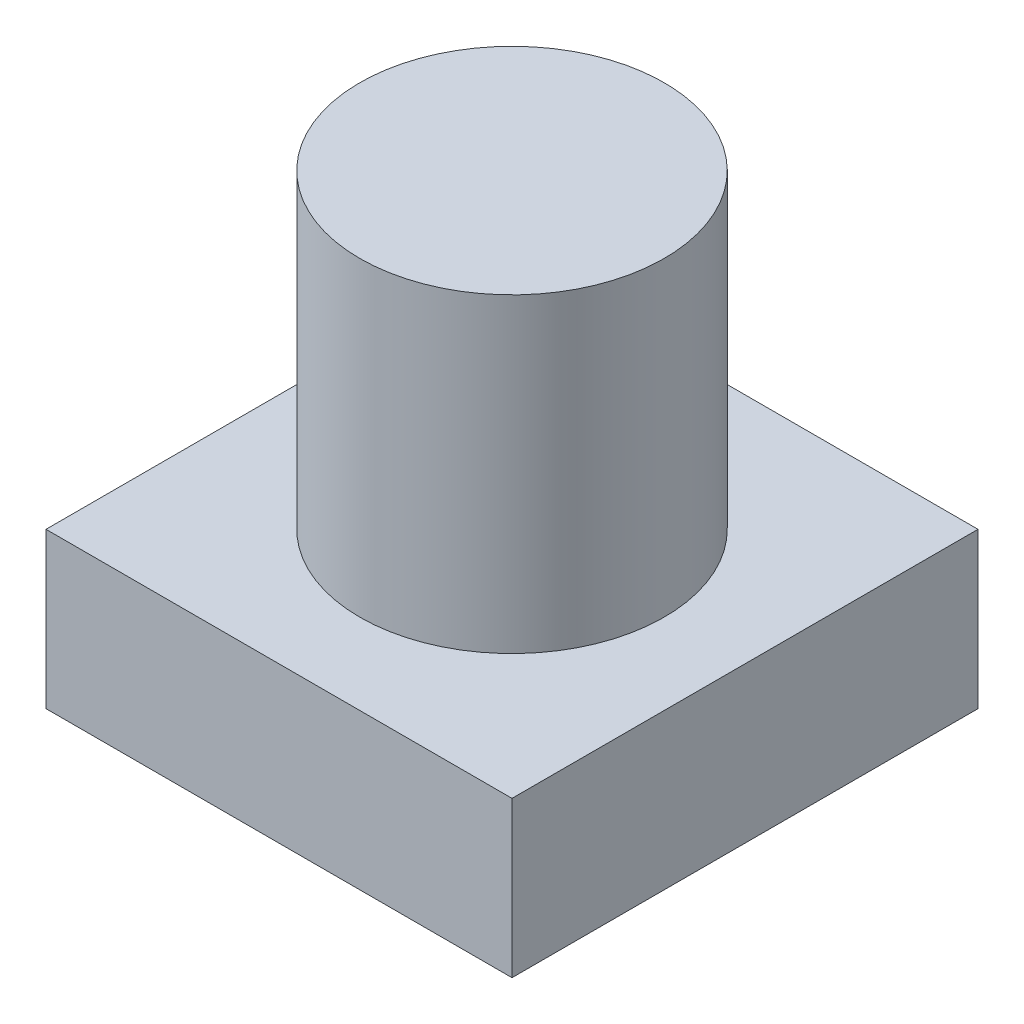
SolidWorks part; units mm, degrees
ref_plane "Front Plane" through (0, 0, 0) normal (0, 0, 1) x (1, 0, 0)
ref_plane "Top Plane" through (0, 0, 0) normal (0, 1, 0) x (1, 0, 0)
ref_plane "Right Plane" through (0, 0, 0) normal (1, 0, 0) x (0, 0, -1)
sketch "Sketch1" plane through (0, 0, 0) normal (0, 1, 0) x (1, 0, 0)
  line L1 (-7.5, -7.5) -> (7.5, -7.5)
  line L2 (-7.5, -7.5) -> (-7.5, 7.5)
  line L3 (-7.5, 7.5) -> (7.5, 7.5)
  line L4 (7.5, -7.5) -> (7.5, 7.5)
  line L5 (-7.5, -7.5) -> (7.5, 7.5) construction
  line L6 (-7.5, 7.5) -> (7.5, -7.5) construction
  point P0 (0, 0)
  dimension "D1" = 15
  dimension "D2" = 15
extrude "Boss-Extrude1" add sketch "Sketch1" along normal blind 5
sketch "Sketch2" plane through (0, 5, 0) normal (0, 1, 0) x (1, 0, 0)
  circle A0 centre (0, 0) radius 4.9
  dimension "D1" = 9.8
extrude "Boss-Extrude2" add sketch "Sketch2" along normal blind 10
